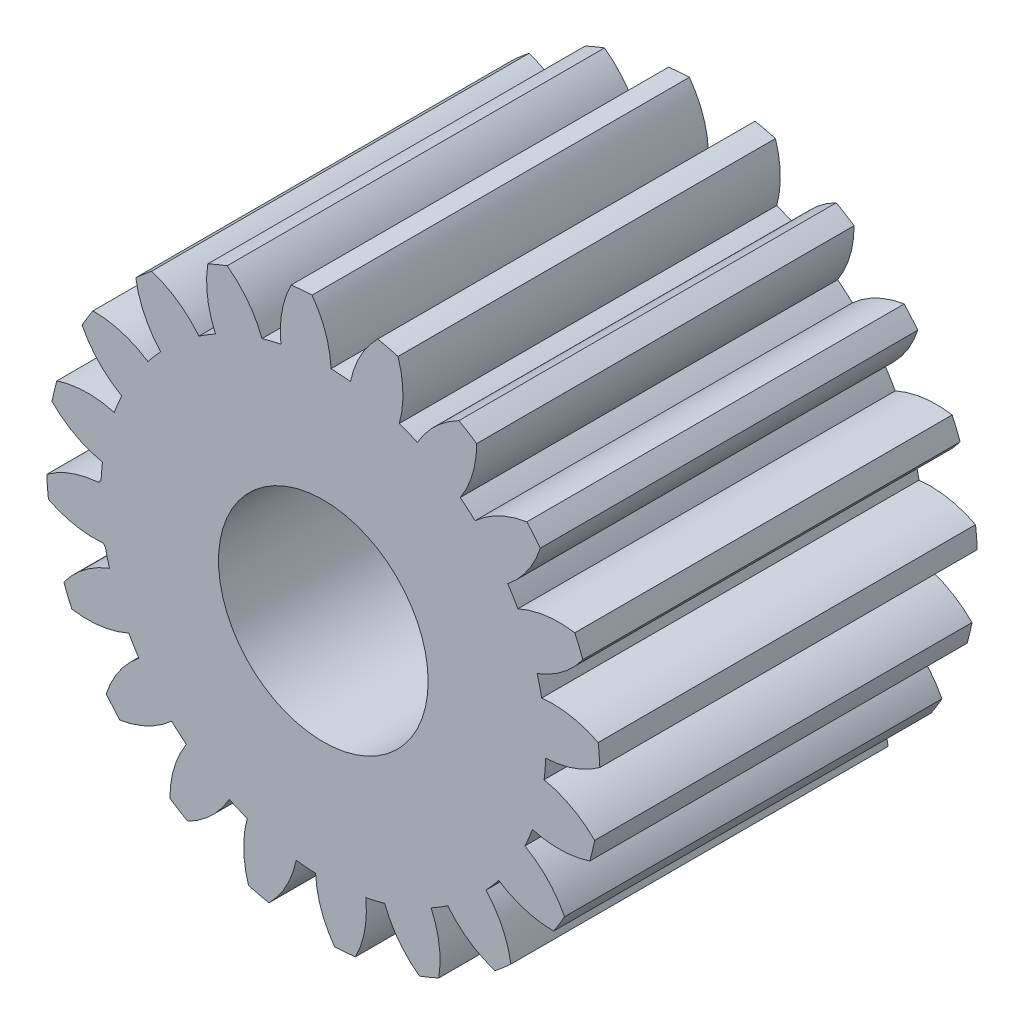
SolidWorks part; units mm, degrees
ref_plane "Front Plane" through (0, 0, 0) normal (0, 0, 1) x (1, 0, 0)
ref_plane "Top Plane" through (0, 0, 0) normal (0, 1, 0) x (1, 0, 0)
ref_plane "Right Plane" through (0, 0, 0) normal (1, 0, 0) x (0, 0, -1)
sketch "Sketch2" plane through (0, 0, 0) normal (0, 0, 1) x (1, 0, 0)
  line L0 (-30, 0) -> (-30, 24.0946)
  line L1 (-30, 0) -> (-20.5388, 25.9945)
  line L2 (-28.1908, 0) -> (-33, 0) construction
  line L3 (-28.1908, 0) -> (-30.5954, 0)
  line L4 (-30.5954, 0) -> (-33, 0)
  line L5 (-30.5954, 0) -> (-25.9752, -10.955) construction
  line L6 (-30.5954, 0) -> (-29.0553, -3.6517)
  line L7 (-29.0553, -3.6517) -> (-27.5152, -7.3033)
  line L8 (-27.5152, -7.3033) -> (-25.9752, -10.955)
  line L9 (-25.9752, -10.955) -> (-24.4351, -14.6066)
  line L10 (0, 0) -> (-32.8983, -2.5892) construction
  line L11 (0, 0) -> (-30.5954, 0) construction
  circle A0 centre (0, 0) radius 30
  circle A1 centre (0, 0) radius 26.5288
  circle A2 centre (0, 0) radius 33
  circle A3 centre (0, 0) radius 28.1908
  arc A4 (-32.9727, -1.3429) -> (-26.5127, 0.9223) centre (-25.9752, -10.955) cw
  arc A5 (-32.7768, -3.8317) -> (-26.042, -5.0584) centre (-27.3691, 6.7567) ccw
  dimension "D1" = 60
  dimension "D2" = 66
  dimension "D3" = 53.0575
  dimension "D4" = 20
  dimension "D6" = 4.5
sketch "Sketch5" plane through (0, 0, 0) normal (0, 0, 1) x (1, 0, 0)
  arc A0 (-26.5127, 0.9223) -> (-32.9727, -1.3429) centre (-25.9752, -10.955) ccw construction
  arc A1 (-26.5127, 0.9223) -> (-32.9727, -1.3429) centre (-25.9752, -10.955) ccw
  arc A2 (-32.7768, -3.8317) -> (-26.042, -5.0584) centre (-27.3691, 6.7567) ccw construction
  arc A3 (-32.7768, -3.8317) -> (-26.042, -5.0584) centre (-27.3691, 6.7567) ccw
  circle A4 centre (0, 0) radius 26.5288 construction
  circle A5 centre (0, 0) radius 33 construction
  arc A6 (-26.5127, 0.9223) -> (-26.042, -5.0584) centre (0, 0) ccw
  arc A7 (-32.9727, -1.3429) -> (-32.7768, -3.8317) centre (0, 0) ccw
extrude "Boss-Extrude3" add sketch "Sketch5" along normal blind 45
extrude "Boss-Extrude4" add sketch "Sketch2" along normal blind 45 contours A1
fillet "Fillet1" radius 0.5 1 edges at (-26.5127, 0.9223, 22.5)
fillet "Fillet3" radius 0.5 1 edges at (-26.042, -5.0584, 22.5)
sketch "Sketch6" plane through (0, 0, 45) normal (0, 0, 1) x (1, 0, 0)
  circle A0 centre (0, 0) radius 12.5
  dimension "D1" = 25
pattern_circular "CirPattern1" count 20 over 360 about axis through (0, 0, 0) along (0, 0, 1) of "Boss-Extrude3"
extrude "Cut-Extrude1" cut sketch "Sketch6" against normal blind 45
equation "\"Teeth\"= 20"
equation "\"Module\"= 3"
equation "\"pcd\"= \"Teeth\" * \"Module\""
equation "\"circularpitch\"= 3.1415 * \"Module\""
equation "\"diametricalpitch\"= 1 / \"Module\""
equation "\"addendum\"= \"Module\""
equation "\"addendumCircularDiameter\"= \"pcd\" + 2 * \"Module\""
equation "\"clearance\"= \"circularpitch\" / \"Teeth\""
equation "\"dedendum\"= \"addendum\" + \"clearance\""
equation "\"dedendumCircularDiameter\"= \"pcd\" - 2 * \"dedendum\""
equation "\"pressureangle\"= 20"
equation "\"circularpitchangle\"= \"circularpitch\" * 360 / ( 3.1415 * \"pcd\" * 4 )"
equation "\"D2@Sketch2\"=\"addendumCircularDiameter\""
equation "\"D1@Sketch2\"=\"pcd\""
equation "\"D3@Sketch2\"=\"dedendumCircularDiameter\""
equation "\"D4@Sketch2\"=\"pressureangle\""
equation "\"D6@Sketch2\"=\"circularpitchangle\""
equation "\"D1@CirPattern1\"=\"Teeth\""
